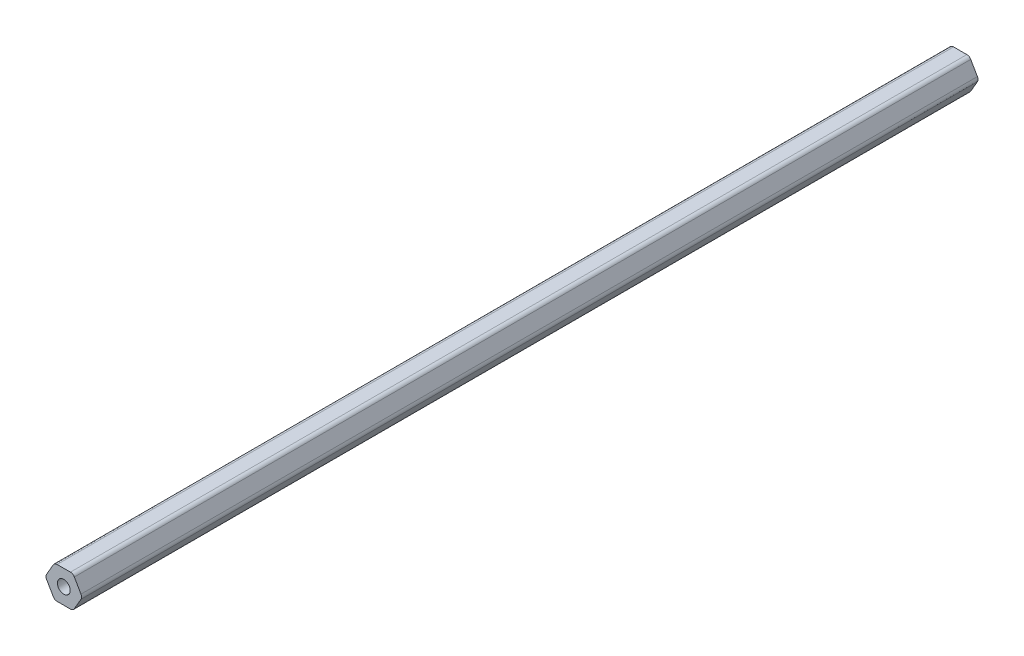
SolidWorks part; units mm, degrees
ref_plane "Front Plane" through (0, 0, 0) normal (0, 0, 1) x (1, 0, 0)
ref_plane "Top Plane" through (0, 0, 0) normal (0, 1, 0) x (1, 0, 0)
ref_plane "Right Plane" through (0, 0, 0) normal (1, 0, 0) x (0, 0, -1)
sketch "Sketch1" plane through (0, 0, 0) normal (0, 0, 1) x (1, 0, 0)
  line L1 (5.605, 0.3701) -> (1.9388, 6.7201)
  line L2 (1.9388, 6.7201) -> (-5.3935, 6.7201)
  line L3 (-5.3935, 6.7201) -> (-9.0597, 0.3701)
  line L4 (-9.0597, 0.3701) -> (-5.3935, -5.9799)
  line L5 (-5.3935, -5.9799) -> (1.9388, -5.9799)
  line L6 (1.9388, -5.9799) -> (5.605, 0.3701)
  circle A0 centre (-1.7273, 0.3701) radius 6.35 construction
  circle A1 centre (-1.7273, 0.3701) radius 2.54
  dimension "D1" = 12.7
extrude "Boss-Extrude1" add sketch "Sketch1" along normal blind 355.6
fillet "Fillet1" radius 1.778 6 edges at (-5.3935, -5.9799, 177.8) (1.9388, -5.9799, 177.8) (5.605, 0.3701, 177.8) (1.9388, 6.7201, 177.8) (-5.3935, 6.7201, 177.8) (-9.0597, 0.3701, 177.8)
